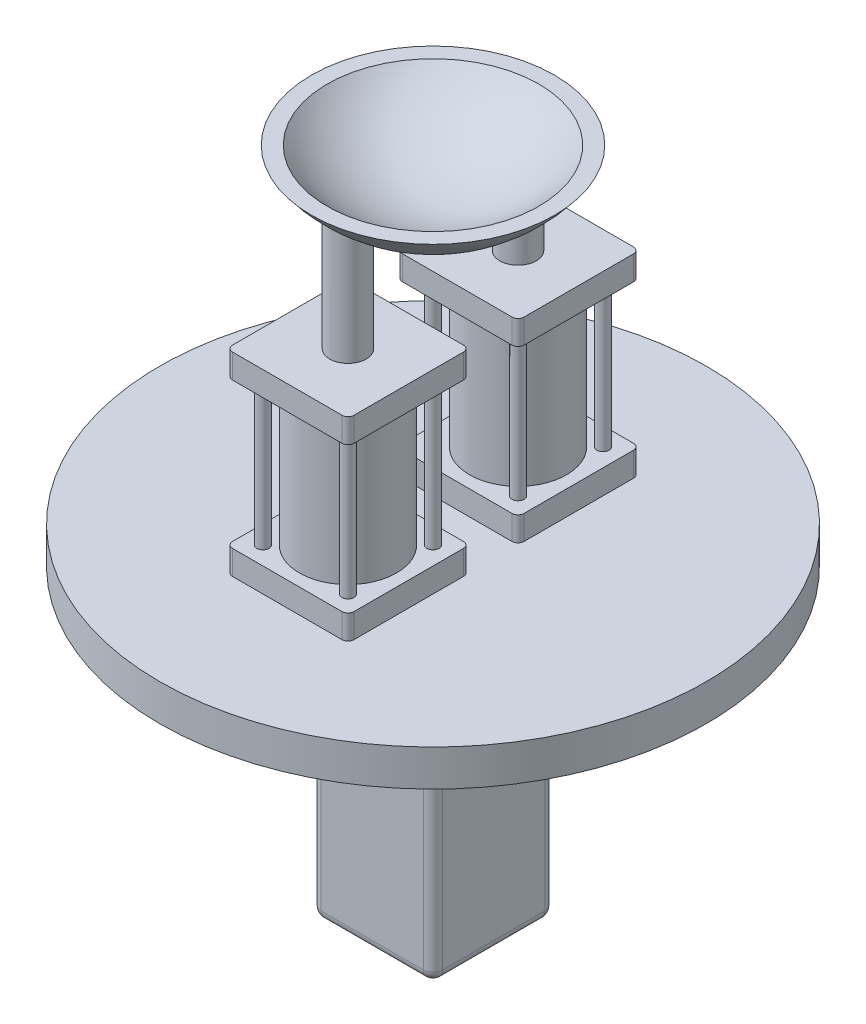
SolidWorks part; units mm, degrees
ref_plane "Front Plane" through (0, 0, 0) normal (0, 0, 1) x (1, 0, 0)
ref_plane "Top Plane" through (0, 0, 0) normal (0, 1, 0) x (1, 0, 0)
ref_plane "Right Plane" through (0, 0, 0) normal (1, 0, 0) x (0, 0, -1)
sketch "Sketch1" plane through (0, 0, 0) normal (0, 1, 0) x (1, 0, 0)
  circle A0 centre (0, 0) radius 225
  dimension "D1" = 450
extrude "Boss-Extrude1" add sketch "Sketch1" along normal blind 30
sketch "Sketch7" plane through (0, 0, 0) normal (1, 0, 0) x (0, 0, -1)
  line L0 (0, 228.9013) -> (0, 0) construction
  line L1 (0, 0) -> (319.3432, 0) construction
  line L2 (0, 250) -> (262.7708, 250) construction
  line L3 (100, 300) -> (0, 300)
  line L4 (0, 300) -> (0, 250)
  arc A0 (0, 250) -> (100, 300) centre (0, 375) ccw
  dimension "D1" = 100
  dimension "D3" = 250
  dimension "D2" = 50
revolve "Revolve1" add sketch "Sketch7" angle 360 about L4
shell "Shell1" thickness 10
sketch "Sketch8" plane through (0, 30, 0) normal (0, 1, 0) x (1, 0, 0)
  line L0 (0, 225) -> (0, 0) construction
  line L1 (0, 0) -> (225, 0) construction
  line L7 (-50, -120) -> (50, -20) construction
  line L8 (-50, 20) -> (50, 20)
  line L12 (-50, 20) -> (-50, 120)
  line L13 (-50, 120) -> (50, 120)
  line L26 (50, 20) -> (50, 120)
  line L27 (-50, 20) -> (50, 120) construction
  line L28 (-50, 120) -> (50, 20) construction
  line L29 (-50, -20) -> (50, -120) construction
  line L30 (50, -20) -> (50, -120)
  line L31 (-50, -120) -> (50, -120)
  line L32 (-50, -20) -> (-50, -120)
  line L33 (-50, -20) -> (50, -20)
  circle A0 centre (0, 0) radius 225 construction
  point P7 (0, 70)
  point P16 (0, -70)
  dimension "D1" = 100
  dimension "D2" = 100
  dimension "D3" = 20
extrude "Boss-Extrude2" add sketch "Sketch8" along normal blind 20 separate body
sketch "Sketch9" plane through (0, 0, 0) normal (0, -1, 0) x (1, 0, 0)
  circle A0 centre (0, 0) radius 17.5
  dimension "D1" = 35
extrude "Boss-Extrude3" add sketch "Sketch9" along normal blind 100 separate body
sketch "Sketch11" plane through (0, -100, 0) normal (0, -1, 0) x (1, 0, 0)
  line L1 (-50, -50) -> (50, -50)
  line L2 (-50, -50) -> (-50, 50)
  line L3 (-50, 50) -> (50, 50)
  line L4 (50, -50) -> (50, 50)
  line L5 (-50, -50) -> (50, 50) construction
  line L6 (-50, 50) -> (50, -50) construction
  point P0 (0, 0)
  dimension "D1" = 100
  dimension "D2" = 100
extrude "Boss-Extrude4" add sketch "Sketch11" along normal blind 150 separate body
fillet "Fillet1" radius 8 4 edges at (-50, -175, 50) (-50, -175, -50) (50, -175, -50) (50, -175, 50)
fillet "Fillet2" radius 8 8 edges at (47.6569, -250, 47.6569) (50, -250, 0) (47.6569, -250, -47.6569) (0, -250, -50) (-47.6569, -250, -47.6569) (-50, -250, 0) (-47.6569, -250, 47.6569) (0, -250, 50)
sketch "Sketch14" plane through (0, 50, 0) normal (0, 1, 0) x (1, 0, 0)
  line L0 (-50, 70) -> (50, 70) construction
  line L1 (-50, 120) -> (-50, 20) construction
  line L2 (50, 20) -> (50, 120) construction
  circle A0 centre (0, 70) radius 40
  dimension "D1" = 80
extrude "Boss-Extrude6" add sketch "Sketch14" along normal blind 120 separate body
sketch "Sketch15" plane through (0, 170, 0) normal (0, 1, 0) x (1, 0, 0)
  line L1 (-50, 120) -> (50, 120)
  line L2 (-50, 120) -> (-50, 20)
  line L3 (-50, 20) -> (50, 20)
  line L4 (50, 120) -> (50, 20)
extrude "Boss-Extrude7" add sketch "Sketch15" along normal blind 20 separate body
mirror "Mirror1" about plane through (0, 0, 0) normal (0, 0, 1) of bodies 117 116
sketch "Sketch16" plane through (0, 190, 0) normal (0, 1, 0) x (1, 0, 0)
  line L0 (-50, 70) -> (50, 70) construction
  line L1 (-50, 120) -> (-50, 20) construction
  line L2 (50, 20) -> (50, 120) construction
  line L3 (0, 0) -> (177.8967, 0) construction
  circle A0 centre (0, 70) radius 15
  circle A1 centre (0, -70) radius 15
  dimension "D1" = 30
extrude "Boss-Extrude8" add sketch "Sketch16" along normal up to surface (72.7503 mm away)
fillet "Fillet3" radius 5 8 edges at (-50, 180, 20) (-50, 180, 120) (50, 180, 120) (50, 180, 20) (50, 180, -20) (-50, 180, -20) (-50, 180, -120) (50, 180, -120)
fillet "Fillet4" radius 5 4 edges at (50, 40, -20) (-50, 40, -20) (-50, 40, -120) (50, 40, -120)
fillet "Fillet5" radius 5 4 edges at (50, 40, 120) (50, 40, 20) (-50, 40, 120) (-50, 40, 20)
sketch "Sketch17" plane through (0, 50, 0) normal (0, 1, 0) x (1, 0, 0)
  line L0 (0, 120) -> (0, 70) construction
  line L1 (45, 120) -> (-45, 120) construction
  line L2 (0, 70) -> (50, 70) construction
  line L3 (50, 25) -> (50, 115) construction
  line L4 (-50, 115) -> (-50, 25) construction
  circle A0 centre (-35, 105) radius 5
  circle A3 centre (35, 105) radius 5
  circle A4 centre (35, 35) radius 5
  circle A5 centre (-35, 35) radius 5
  dimension "D1" = 10
  dimension "D2" = 15
  dimension "D3" = 15
extrude "Boss-Extrude9" add sketch "Sketch17" along normal up to surface (120 mm away) separate body up to face at (0, 170, -70)
mirror "Mirror3" about plane through (0, 0, 0) normal (0, 0, 1) of bodies 123 126 125 124
